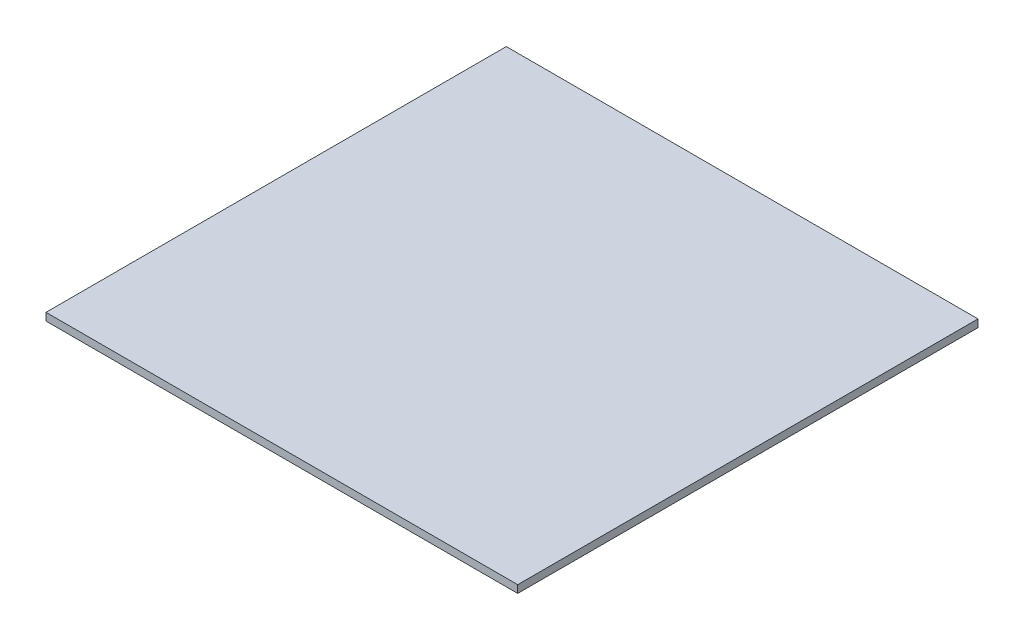
SolidWorks part; units mm, degrees
ref_plane "Front Plane" through (0, 0, 0) normal (0, 0, 1) x (1, 0, 0)
ref_plane "Top Plane" through (0, 0, 0) normal (0, 1, 0) x (1, 0, 0)
ref_plane "Right Plane" through (0, 0, 0) normal (1, 0, 0) x (0, 0, -1)
sketch "Sketch1" plane through (0, 0, 0) normal (0, 1, 0) x (1, 0, 0)
  line L1 (-248, -242) -> (248, -242)
  line L2 (-248, -242) -> (-248, 242)
  line L3 (-248, 242) -> (248, 242)
  line L4 (248, -242) -> (248, 242)
  line L5 (-248, -242) -> (248, 242) construction
  line L6 (-248, 242) -> (248, -242) construction
  point P0 (0, 0)
  dimension "D1" = 496
  dimension "D2" = 484
extrude "Boss-Extrude1" add sketch "Sketch1" along normal blind 8
